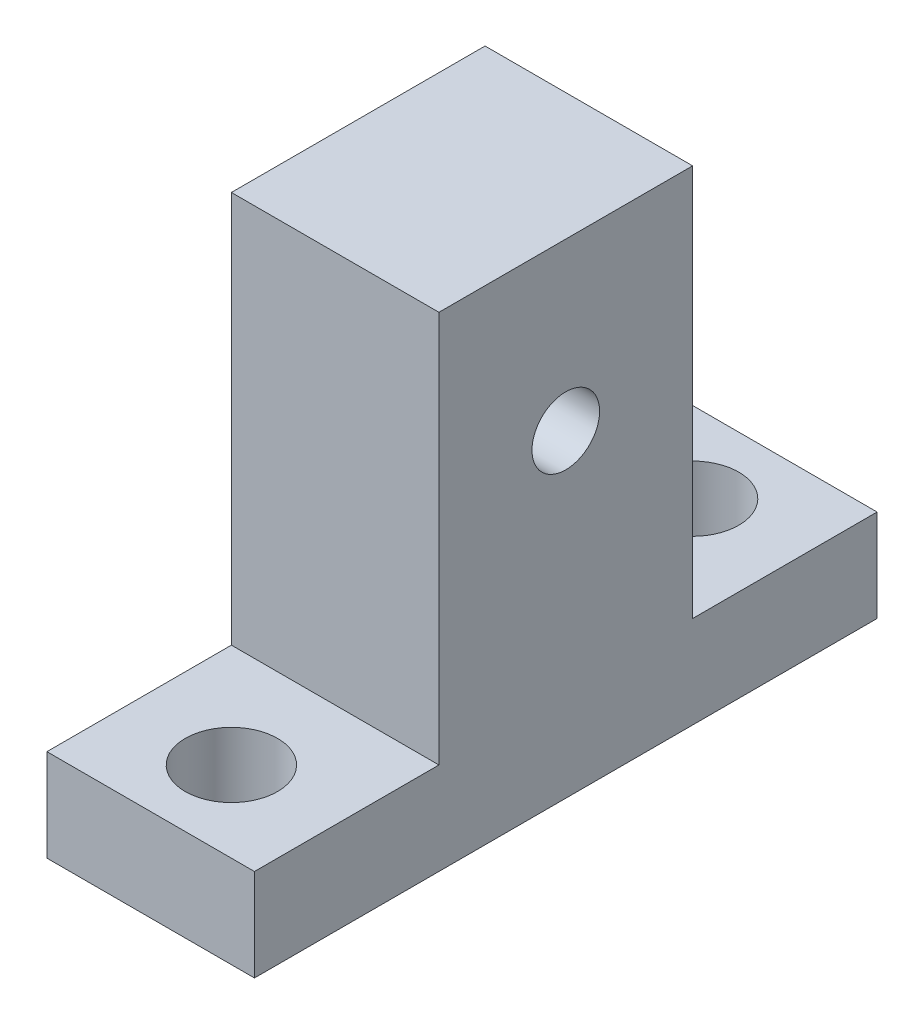
SolidWorks part; units mm, degrees
ref_plane "Front Plane" through (0, 0, 0) normal (0, 0, 1) x (1, 0, 0)
ref_plane "Top Plane" through (0, 0, 0) normal (0, 1, 0) x (1, 0, 0)
ref_plane "Right Plane" through (0, 0, 0) normal (1, 0, 0) x (0, 0, -1)
sketch "Sketch1" plane through (0, 0, 0) normal (1, 0, 0) x (0, 0, -1)
  line L0 (0, 0) -> (42.8625, 0)
  line L1 (42.8625, 0) -> (42.8625, 6.35)
  line L2 (42.8625, 6.35) -> (30.1625, 6.35)
  line L3 (30.1625, 6.35) -> (30.1625, 33.3375)
  line L4 (30.1625, 33.3375) -> (12.7, 33.3375)
  line L5 (12.7, 33.3375) -> (12.7, 6.35)
  line L6 (12.7, 6.35) -> (0, 6.35)
  line L7 (0, 6.35) -> (0, 0)
  line L8 (21.4312, 21.9075) -> (21.4312, 33.3375) construction
  circle A0 centre (21.4312, 21.9075) radius 2.3283
  dimension "D5" = 4.6567
  dimension "D1" = 12.7
  dimension "D2" = 26.9875
  dimension "D3" = 6.35
  dimension "D4" = 17.4625
  dimension "D6" = 11.43
extrude "Boss-Extrude1" add sketch "Sketch1" along normal blind 14.2875
sketch "Sketch2" plane through (0, 6.35, 0) normal (0, 1, 0) x (1, 0, 0)
  line L0 (7.1437, 0) -> (7.1437, 50000) construction
  line L1 (14.2875, 0) -> (0, 0) construction
  line L2 (14.2875, 42.8625) -> (0, 42.8625) construction
  line L3 (7.1437, 5.5562) -> (7.1437, 37.3062) construction
  line L4 (14.2875, 0) -> (14.2875, 42.8625) construction
  line L5 (14.2875, 0) -> (14.2875, 42.8625) construction
  line L6 (7.1437, 5.5562) -> (7.1437, 37.3062) construction
  line L7 (7.1437, 21.4312) -> (14.2875, 21.4312) construction
  circle A0 centre (7.1437, 5.5562) radius 3.175
  circle A1 centre (7.1437, 37.3062) radius 3.175
  point P8 (7.1437, 0)
  point P11 (7.1437, 42.8625)
  point P16 (7.1437, 20.8734)
  dimension "D1" = 6.35
  dimension "D2" = 6.35
  dimension "D3" = 31.75
extrude "Cut-Extrude1" cut sketch "Sketch2" against normal blind 14.2875
